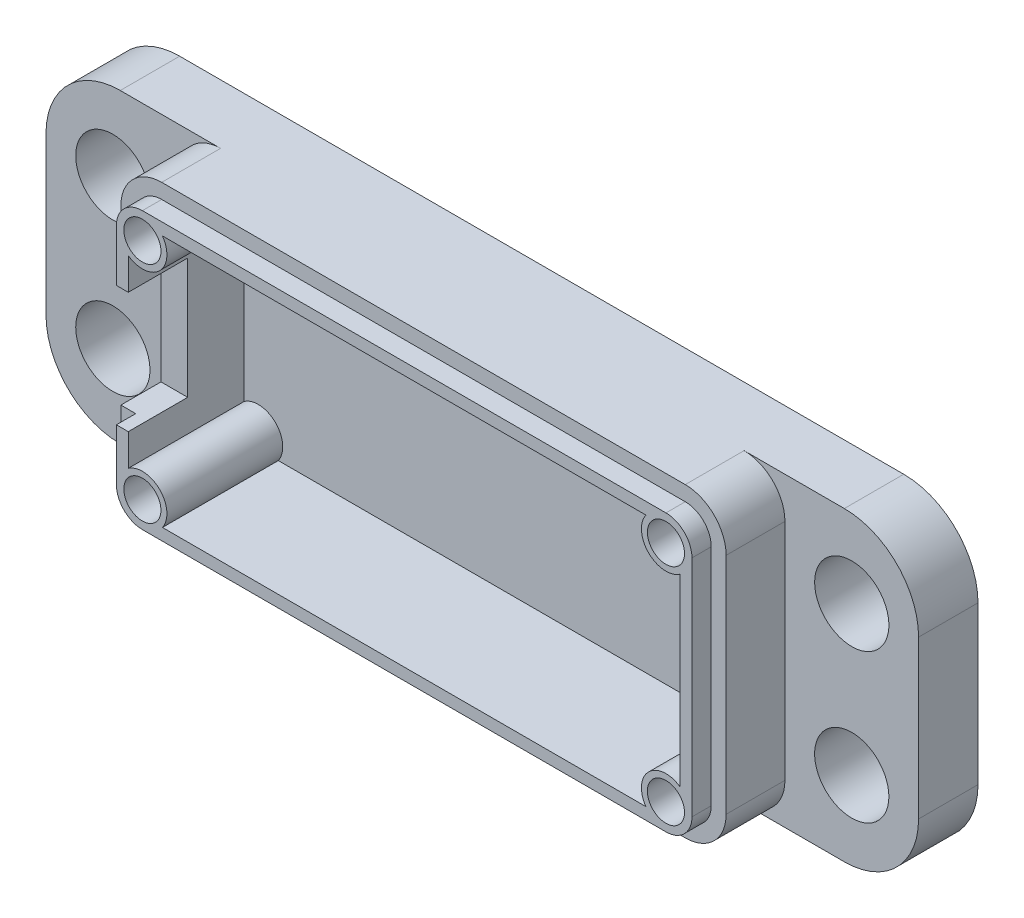
SolidWorks part; units mm, degrees
ref_plane "Front Plane" through (0, 0, 0) normal (0, 0, 1) x (1, 0, 0)
ref_plane "Top Plane" through (0, 0, 0) normal (0, 1, 0) x (1, 0, 0)
ref_plane "Right Plane" through (0, 0, 0) normal (1, 0, 0) x (0, 0, -1)
sketch "Esquisse1" plane through (0, 0, 0) normal (0, 0, 1) x (1, 0, 0)
  line L1 (-40.75, 20.6) -> (0, 20.6)
  line L2 (-40.75, 20.6) -> (-40.75, 0)
  line L3 (-40.75, 0) -> (0, 0)
  line L4 (0, 20.6) -> (0, 0)
  dimension "D1" = 40.75
  dimension "D2" = 20.6
extrude "Extrusion1" add sketch "Esquisse1" along normal blind 9.26
sketch "Esquisse2" plane through (0, 0, 9.26) normal (0, 0, 1) x (1, 0, 0)
  line L0 (-20.375, 22.9979) -> (-20.375, -4.2121) construction
  line L1 (-46.4668, 10.3) -> (2.5983, 10.3) construction
  line L2 (0, 20.6) -> (-40.75, 20.6) construction
  line L3 (-40.75, 0) -> (0, 0) construction
  line L4 (-40.75, 20.6) -> (-40.75, 0) construction
  line L5 (0, 0) -> (0, 20.6) construction
  circle A0 centre (-38, 17.85) radius 1.25
  circle A1 centre (-38, 2.75) radius 1.25
  circle A2 centre (-2.75, 2.75) radius 1.25
  circle A3 centre (-2.75, 17.85) radius 1.25
  dimension "D1" = 2.5
  dimension "D2" = 2.75
  dimension "D3" = 2.75
extrude "Extrusion2" cut sketch "Esquisse2" against normal through all
sketch "Esquisse4" plane through (0, 0, 0) normal (0, 0, -1) x (-1, 0, 0)
  line L0 (20.375, 25.7736) -> (20.375, -8.5848) construction
  line L1 (-5.7073, 10.3) -> (58.4286, 10.3) construction
  line L2 (0, 0) -> (0, 20.6) construction
  line L3 (40.75, 20.6) -> (40.75, 0) construction
  line L4 (0, 20.6) -> (40.75, 20.6) construction
  line L5 (40.75, 0) -> (0, 0) construction
  line L6 (2.75, 20.6) -> (38, 20.6)
  line L7 (0, 17.85) -> (0, 2.75)
  line L8 (2.75, 0) -> (38, 0)
  line L9 (40.75, 17.85) -> (40.75, 2.75)
  arc A0 (2.75, 20.6) -> (0, 17.85) centre (2.75, 17.85) ccw
  circle A1 centre (2.75, 17.85) radius 1.25 construction
  arc A2 (2.75, 0) -> (0, 2.75) centre (2.75, 2.75) cw
  arc A3 (38, 0) -> (40.75, 2.75) centre (38, 2.75) ccw
  arc A4 (38, 20.6) -> (40.75, 17.85) centre (38, 17.85) cw
  point P19 (20.375, 20.6)
  point P22 (0, 10.3)
  point P29 (40.75, 10.3)
  point P30 (20.375, 0)
extrude "Extrusion5" cut sketch "Esquisse4" against normal through all flip side to cut
sketch "Esquisse3" plane through (0, 0, 9.26) normal (0, 0, 1) x (1, 0, 0)
  line L0 (-45.5809, 10.3) -> (6.4112, 10.3) construction
  line L1 (-20.375, 23.8416) -> (-20.375, -7.4043) construction
  line L2 (-40.75, 17.85) -> (-40.75, 2.75) construction
  line L3 (0, 2.75) -> (0, 17.85) construction
  line L4 (-38, 0) -> (-2.75, 0) construction
  line L5 (-2.75, 20.6) -> (-38, 20.6) construction
  line L6 (-38, 19.6) -> (-2.75, 19.6)
  line L7 (-39.75, 17.85) -> (-39.75, 2.75)
  line L8 (-38, 20.6) -> (-2.75, 20.6)
  line L9 (-40.75, 17.85) -> (-40.75, 2.75) construction
  line L10 (-2.75, 20.6) -> (-38, 20.6) construction
  line L11 (-40.75, 17.85) -> (-40.75, 2.75)
  line L12 (-38, 0) -> (-2.75, 0)
  line L13 (-38, 1) -> (-2.75, 1)
  line L14 (0, 17.85) -> (0, 2.75)
  line L15 (-1, 17.85) -> (-1, 2.75)
  arc A0 (-38, 19.6) -> (-39.75, 17.85) centre (-38, 17.85) ccw
  arc A1 (-38, 20.6) -> (-40.75, 17.85) centre (-38, 17.85) ccw
  arc A2 (-38, 20.6) -> (-40.75, 17.85) centre (-38, 17.85) ccw construction
  arc A3 (-38, 0) -> (-40.75, 2.75) centre (-38, 2.75) cw
  arc A4 (-38, 1) -> (-39.75, 2.75) centre (-38, 2.75) cw
  circle A5 centre (-38, 17.85) radius 1.25 construction
  arc A6 (-2.75, 1) -> (-1, 2.75) centre (-2.75, 2.75) ccw
  arc A7 (-2.75, 0) -> (0, 2.75) centre (-2.75, 2.75) ccw
  arc A8 (-2.75, 20.6) -> (0, 17.85) centre (-2.75, 17.85) cw
  arc A9 (-2.75, 19.6) -> (-1, 17.85) centre (-2.75, 17.85) cw
  point P20 (-20.375, 19.6)
  point P27 (-39.75, 10.3)
  point P30 (-20.375, 19.6)
  point P32 (-20.375, 20.6)
  point P34 (-1, 10.3)
  point P35 (-20.375, 1)
  point P36 (-20.375, 0)
  point P40 (-40.75, 10.3)
  point P41 (-39.75, 10.3)
  point P52 (0, 10.3)
  point P53 (-20.375, 1)
  dimension "D1" = 1
extrude "Extrusion4" cut sketch "Esquisse3" against normal blind 1.3
sketch "Esquisse6" plane through (0, 0, 9.26) normal (0, 0, 1) x (1, 0, 0)
  line L0 (-47.3868, 10.3) -> (4.3212, 10.3) construction
  line L1 (-20.375, 22.3803) -> (-20.375, -4.0789) construction
  line L5 (-2.75, 20.6) -> (-38, 20.6) construction
  line L6 (-38, 0) -> (-2.75, 0) construction
  line L7 (-40.75, 17.85) -> (-40.75, 2.75) construction
  line L8 (0, 2.75) -> (0, 17.85) construction
  line L9 (-36.6509, 18.8) -> (-4.0991, 18.8)
  line L10 (-38.95, 16.5009) -> (-38.95, 4.0991)
  line L11 (-2.75, 19.6) -> (-38, 19.6) construction
  line L12 (-39.75, 17.85) -> (-39.75, 2.75) construction
  line L13 (-36.6509, 1.8) -> (-4.0991, 1.8)
  line L14 (-1.8, 16.5009) -> (-1.8, 4.0991)
  arc A0 (-38.95, 16.5009) -> (-36.6509, 18.8) centre (-38, 17.85) ccw
  circle A1 centre (-38, 17.85) radius 1.25 construction
  arc A2 (-38.95, 4.0991) -> (-36.6509, 1.8) centre (-38, 2.75) cw
  arc A3 (-1.8, 4.0991) -> (-4.0991, 1.8) centre (-2.75, 2.75) ccw
  arc A4 (-1.8, 16.5009) -> (-4.0991, 18.8) centre (-2.75, 17.85) cw
  point P19 (-20.375, 18.8)
  point P26 (-38.95, 10.3)
  point P33 (-1.8, 10.3)
  point P34 (-20.375, 1.8)
  dimension "D3" = 3.3
  dimension "D1" = 0.8
  dimension "D2" = 0.8
extrude "Extrusion9" cut sketch "Esquisse6" against normal blind 7.8
sketch "Esquisse7" plane through (-40.75, 0, 0) normal (-1, 0, 0) x (0, 0, 1)
  line L0 (-6.9512, 10.3) -> (15.4108, 10.3) construction
  line L1 (7.96, 2.75) -> (0, 2.75) construction
  line L2 (7.96, 17.85) -> (0, 17.85) construction
  line L3 (5.26, 14.362) -> (9.26, 14.362)
  line L4 (9.26, 17.85) -> (9.26, 2.75) construction
  line L5 (5.26, 14.362) -> (5.26, 6.238)
  line L6 (7.96, 17.85) -> (7.96, 2.75) construction
  line L7 (9.26, 14.362) -> (9.26, 6.238)
  line L8 (5.26, 6.238) -> (9.26, 6.238)
  point P15 (9.26, 10.3)
  point P16 (5.26, 10.3)
  dimension "D1" = 4
extrude "Extrusion10" cut sketch "Esquisse7" against normal up to surface (1.8 mm away) up to face at (-38.95, 10.3, 5.36)
sketch "Esquisse8" plane through (0, 0, 0) normal (0, 0, -1) x (-1, 0, 0)
  line L0 (20.375, 24.9147) -> (20.375, -5.082) construction
  line L1 (0, 2.75) -> (0, 17.85) construction
  line L2 (40.75, 17.85) -> (40.75, 2.75) construction
  line L3 (-5.3274, 10.3) -> (47.7683, 10.3) construction
  line L4 (38, 0) -> (2.75, 0) construction
  line L5 (2.75, 20.6) -> (38, 20.6) construction
  line L6 (-9, 20.6) -> (2.75, 20.6)
  line L7 (-9, 20.6) -> (-9, 0)
  line L8 (0, 17.85) -> (0, 2.75)
  line L9 (-9, 0) -> (2.75, 0)
  line L10 (49.75, 0) -> (38, 0)
  line L11 (40.75, 17.85) -> (40.75, 2.75)
  line L12 (49.75, 20.6) -> (49.75, 0)
  line L13 (49.75, 20.6) -> (38, 20.6)
  arc A0 (2.75, 20.6) -> (0, 17.85) centre (2.75, 17.85) ccw construction
  arc A1 (2.75, 20.6) -> (0, 17.85) centre (2.75, 17.85) ccw
  circle A2 centre (-4.5, 15.3) radius 2.5
  circle A3 centre (-4.5, 5.3) radius 2.5
  arc A4 (2.75, 0) -> (0, 2.75) centre (2.75, 2.75) cw
  arc A5 (38, 0) -> (40.75, 2.75) centre (38, 2.75) ccw
  circle A6 centre (45.25, 5.3) radius 2.5
  circle A7 centre (45.25, 15.3) radius 2.5
  arc A8 (38, 20.6) -> (40.75, 17.85) centre (38, 17.85) cw
  point P28 (0, 10.3)
  point P29 (-9, 10.3)
  point P39 (49.75, 10.3)
  point P40 (40.75, 10.3)
  dimension "D1" = 5
  dimension "D2" = 4.5
  dimension "D3" = 9
  dimension "D4" = 5
extrude "Extrusion11" add sketch "Esquisse8" against normal blind 4
fillet "Congé1" radius 5 4 edges at (-49.75, 20.6, 2) (-49.75, 0, 2) (9, 0, 2) (9, 20.6, 2)
sketch "Esquisse9" plane through (0, 0, 0) normal (0, 0, -1) x (-1, 0, 0)
  circle A0 centre (2.75, 17.85) radius 2.1
  circle A1 centre (38, 17.85) radius 2.1
  circle A2 centre (38, 2.75) radius 2.1
  circle A3 centre (2.75, 2.75) radius 2.1
  circle A6 centre (2.75, 2.75) radius 1.25 construction
  circle A7 centre (2.75, 17.85) radius 1.25 construction
  circle A8 centre (38, 17.85) radius 1.25 construction
  circle A9 centre (38, 2.75) radius 1.25 construction
  dimension "D1" = 4.2
extrude "Extrusion12" cut sketch "Esquisse9" against normal blind 1.3
